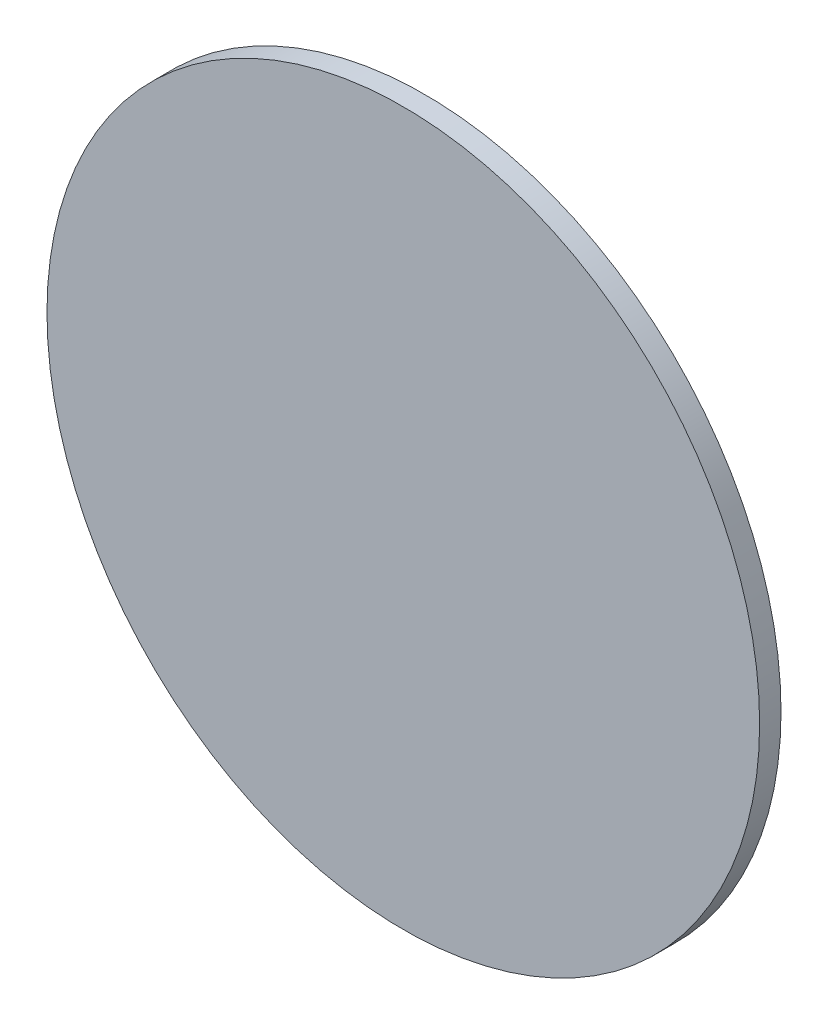
SolidWorks part; units mm, degrees
ref_plane "前基準面" through (0, 0, 0) normal (0, 0, 1) x (1, 0, 0)
ref_plane "上基準面" through (0, 0, 0) normal (0, 1, 0) x (1, 0, 0)
ref_plane "右基準面" through (0, 0, 0) normal (1, 0, 0) x (0, 0, -1)
sketch "草圖1" plane through (0, 0, 0) normal (0, 0, 1) x (1, 0, 0)
  circle A0 centre (0, 0) radius 50
  dimension "D1" = 100
extrude "填料-伸長1" add sketch "草圖1" along normal blind 3
